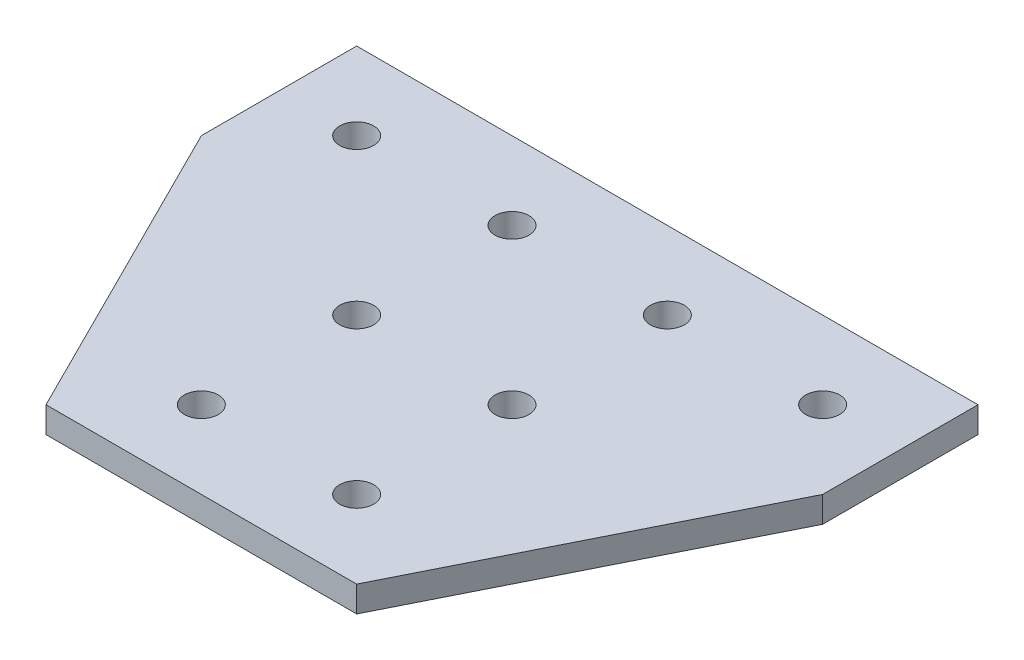
SolidWorks part; units mm, degrees
material "6105-T5 Aluminum"
ref_plane "Front Plane" through (0, 0, 0) normal (0, 0, 1) x (1, 0, 0)
ref_plane "Top Plane" through (0, 0, 0) normal (0, 1, 0) x (1, 0, 0)
ref_plane "Right Plane" through (0, 0, 0) normal (1, 0, 0) x (0, 0, -1)
sketch "Sketch1" plane through (0, 0, 0) normal (0, 1, 0) x (1, 0, 0)
  line L0 (0, 0) -> (-152.4, 0)
  line L1 (-152.4, 0) -> (-152.4, -38.1)
  line L2 (-152.4, -38.1) -> (-114.3, -114.3)
  line L3 (-114.3, -114.3) -> (-38.1, -114.3)
  line L4 (-38.1, -114.3) -> (0, -38.1)
  line L5 (0, -38.1) -> (0, 0)
  circle A0 centre (-95.25, -95.25) radius 4.1656
  circle A1 centre (-95.25, -57.15) radius 4.1656
  circle A2 centre (-133.35, -19.05) radius 4.1656
  circle A3 centre (-95.25, -19.05) radius 4.1656
  circle A4 centre (-57.15, -57.15) radius 4.1656
  circle A5 centre (-57.15, -95.25) radius 4.1656
  circle A6 centre (-57.15, -19.05) radius 4.1656
  circle A7 centre (-19.05, -19.05) radius 4.1656
  dimension "D1" = 8.3312
  dimension "D2" = 8.3312
  dimension "D3" = 8.3312
  dimension "D4" = 8.3312
  dimension "D5" = 8.3312
  dimension "D6" = 8.3312
  dimension "D7" = 8.3312
  dimension "D8" = 8.3312
  dimension "D9" = 19.05
  dimension "D10" = 38.1
  dimension "D11" = 57.15
  dimension "D12" = 95.25
  dimension "D13" = 114.3
  dimension "D14" = 133.35
  dimension "D15" = 152.4
  dimension "D16" = 19.05
  dimension "D17" = 57.15
  dimension "D18" = 76.2
  dimension "D19" = 95.25
  dimension "D20" = 114.3
extrude "Boss-Extrude1" add sketch "Sketch1" against normal blind 6.35
